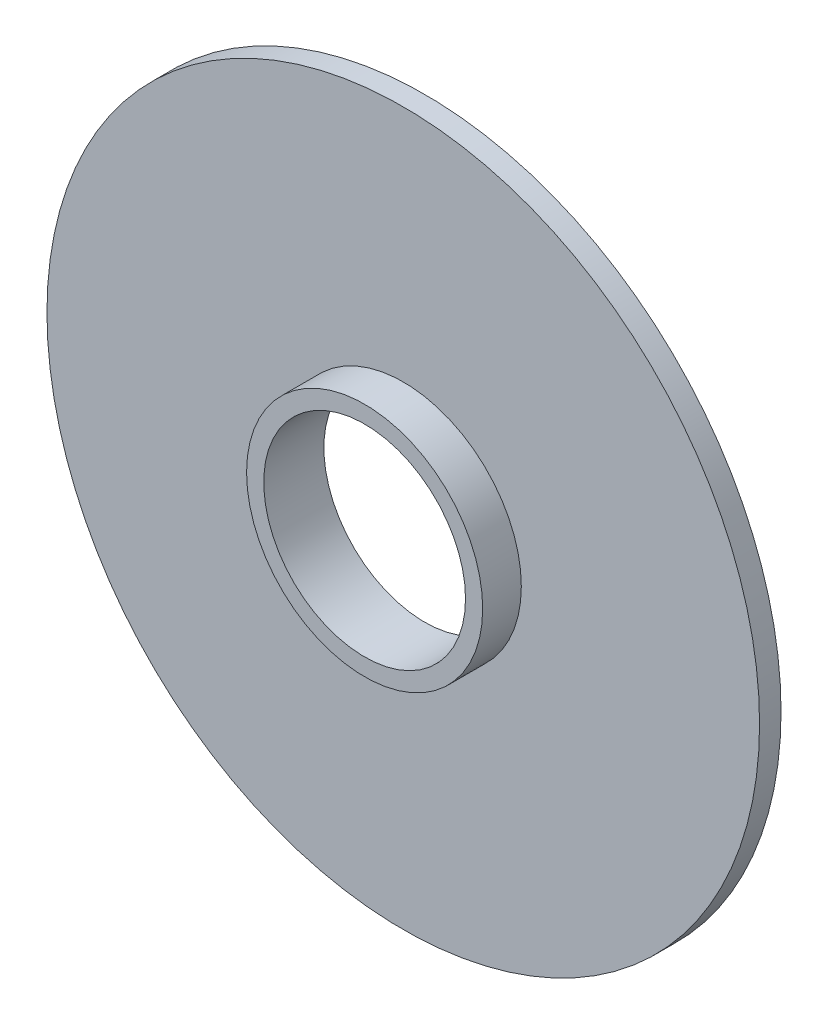
SolidWorks part; units mm, degrees
ref_plane "Спереди" through (0, 0, 0) normal (0, 0, 1) x (1, 0, 0)
ref_plane "Сверху" through (0, 0, 0) normal (0, 1, 0) x (1, 0, 0)
ref_plane "Справа" through (0, 0, 0) normal (1, 0, 0) x (0, 0, -1)
sketch "Эскиз1" plane through (0, 0, 0) normal (0, 0, 1) x (1, 0, 0)
  circle A0 centre (0, 0) radius 83
  circle A1 centre (0, 0) radius 23.5
extrude "Cover_web" add sketch "Эскиз1" along normal blind 5 from offset 40
sketch "Эскиз2" plane through (0, 0, 0) normal (0, 0, 1) x (1, 0, 0)
  circle A0 centre (0, 0) radius 27.5
  circle A1 centre (0, 0) radius 23.5
extrude "Bearing_boss" add sketch "Эскиз2" along normal blind 14 from offset 40
